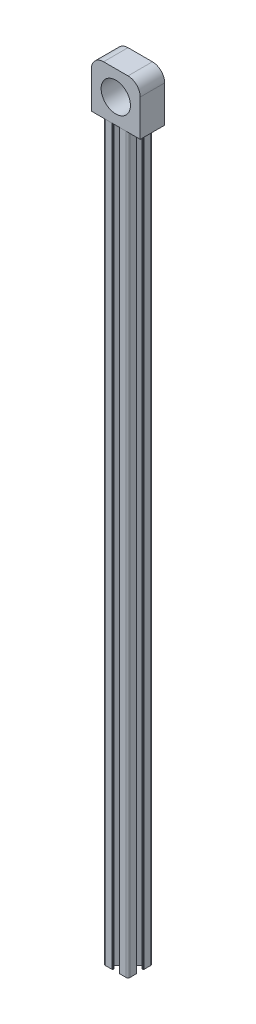
SolidWorks part; units mm, degrees
material "6061-O (SS)"
ref_plane "Front Plane" through (0, 0, 0) normal (0, 0, 1) x (1, 0, 0)
ref_plane "Top Plane" through (0, 0, 0) normal (0, 1, 0) x (1, 0, 0)
ref_plane "Right Plane" through (0, 0, 0) normal (1, 0, 0) x (0, 0, -1)
sketch "Sketch1" plane through (0, 0, 0) normal (0, 1, 0) x (1, 0, 0)
  line L0 (9.4949, 2.6581) -> (9.0109, 2.6581)
  line L1 (8.5029, 3.1661) -> (8.5029, 5.5151)
  line L2 (10.0029, 3.1661) -> (10.0029, 8.5281)
  line L3 (3.6579, -2.3558) -> (3.6579, 2.412)
  line L4 (7.269, 6.0231) -> (7.9949, 6.0231)
  line L5 (6.9098, 5.8743) -> (3.8067, 2.7712)
  line L6 (9.4949, -2.6019) -> (9.0109, -2.6019)
  line L7 (10.0029, -3.1099) -> (10.0029, -8.4719)
  line L8 (8.5029, -3.1099) -> (8.5029, -5.4589)
  line L9 (7.269, -5.9669) -> (7.9949, -5.9669)
  line L10 (6.9098, -5.8181) -> (3.8067, -2.715)
  line L11 (2.1278, -2.2764) -> (2.3074, -2.0968)
  line L12 (-2.6271, 9.5201) -> (-2.6271, 9.0361)
  line L13 (-3.1351, 10.0281) -> (-8.4971, 10.0281)
  line L14 (-3.1351, 8.5281) -> (-5.4841, 8.5281)
  line L15 (2.3868, 3.6831) -> (-2.381, 3.6831)
  line L16 (-5.9921, 7.2942) -> (-5.9921, 8.0201)
  line L17 (-5.8433, 6.935) -> (-2.7402, 3.8319)
  line L18 (2.6329, 9.5201) -> (2.6329, 9.0361)
  line L19 (3.1409, 10.0281) -> (8.5029, 10.0281)
  line L20 (3.1409, 8.5281) -> (5.4899, 8.5281)
  line L21 (5.9979, 7.2942) -> (5.9979, 8.0201)
  line L22 (5.8491, 6.935) -> (2.746, 3.8319)
  line L23 (2.3074, 2.153) -> (2.1278, 2.3326)
  line L24 (-9.4891, -2.6019) -> (-9.0051, -2.6019)
  line L25 (-9.9971, -3.1099) -> (-9.9971, -8.4719)
  line L26 (-8.4971, -3.1099) -> (-8.4971, -5.4589)
  line L27 (-3.6521, 2.412) -> (-3.6521, -2.3558)
  line L28 (-7.2632, -5.9669) -> (-7.9891, -5.9669)
  line L29 (-6.904, -5.8181) -> (-3.8009, -2.715)
  line L30 (-9.4891, 2.6581) -> (-9.0051, 2.6581)
  line L31 (-9.9971, 3.1661) -> (-9.9971, 8.5281)
  line L32 (-8.4971, 3.1661) -> (-8.4971, 5.5151)
  line L33 (-7.2632, 6.0231) -> (-7.9891, 6.0231)
  line L34 (-6.904, 5.8743) -> (-3.8009, 2.7712)
  line L35 (-2.122, 2.3326) -> (-2.3016, 2.153)
  line L36 (2.6329, -9.4639) -> (2.6329, -8.9799)
  line L37 (3.1409, -9.9719) -> (8.5029, -9.9719)
  line L38 (3.1409, -8.4719) -> (5.4899, -8.4719)
  line L39 (-2.381, -3.6269) -> (2.3868, -3.6269)
  line L40 (5.9979, -7.238) -> (5.9979, -7.9639)
  line L41 (5.8491, -6.8788) -> (2.746, -3.7757)
  line L42 (-2.6271, -9.4639) -> (-2.6271, -8.9799)
  line L43 (-3.1351, -9.9719) -> (-8.4971, -9.9719)
  line L44 (-3.1351, -8.4719) -> (-5.4841, -8.4719)
  line L45 (-5.9921, -7.238) -> (-5.9921, -7.9639)
  line L46 (-5.8433, -6.8788) -> (-2.7402, -3.7757)
  line L47 (-2.3016, -2.0968) -> (-2.122, -2.2764)
  arc A0 (-0.8011, -1.9071) -> (0.8069, -1.9071) centre (0.0029, 0.0281) ccw
  arc A1 (8.5029, 5.5151) -> (7.9949, 6.0231) centre (7.9949, 5.5151) ccw
  arc A2 (7.269, 6.0231) -> (6.9098, 5.8743) centre (7.269, 5.5151) ccw
  arc A3 (3.8067, 2.7712) -> (3.6579, 2.412) centre (4.1659, 2.412) ccw
  arc A4 (3.6579, -2.3558) -> (3.8067, -2.715) centre (4.1659, -2.3558) ccw
  arc A5 (6.9098, -5.8181) -> (7.269, -5.9669) centre (7.269, -5.4589) ccw
  arc A6 (7.9949, -5.9669) -> (8.5029, -5.4589) centre (7.9949, -5.4589) ccw
  arc A7 (9.0109, -2.6019) -> (8.5029, -3.1099) centre (9.0109, -3.1099) ccw
  arc A8 (10.0029, -3.1099) -> (9.4949, -2.6019) centre (9.4949, -3.1099) ccw
  arc A9 (9.4949, 2.6581) -> (10.0029, 3.1661) centre (9.4949, 3.1661) ccw
  arc A10 (8.5029, 3.1661) -> (9.0109, 2.6581) centre (9.0109, 3.1661) ccw
  arc A11 (0.8069, -1.9071) -> (2.1278, -2.2764) centre (1.5713, -1.7199) ccw
  arc A12 (2.3074, -2.0968) -> (1.9381, -0.7759) centre (1.7509, -1.5403) ccw
  arc A13 (-2.6271, 9.5201) -> (-3.1351, 10.0281) centre (-3.1351, 9.5201) ccw
  arc A14 (-3.1351, 8.5281) -> (-2.6271, 9.0361) centre (-3.1351, 9.0361) ccw
  arc A15 (1.9381, -0.7759) -> (1.9381, 0.8321) centre (0.0029, 0.0281) ccw
  arc A16 (-2.7402, 3.8319) -> (-2.381, 3.6831) centre (-2.381, 4.1911) ccw
  arc A17 (-5.4841, 8.5281) -> (-5.9921, 8.0201) centre (-5.4841, 8.0201) ccw
  arc A18 (-5.9921, 7.2942) -> (-5.8433, 6.935) centre (-5.4841, 7.2942) ccw
  arc A19 (2.6329, 9.0361) -> (3.1409, 8.5281) centre (3.1409, 9.0361) ccw
  arc A20 (3.1409, 10.0281) -> (2.6329, 9.5201) centre (3.1409, 9.5201) ccw
  arc A21 (5.9979, 8.0201) -> (5.4899, 8.5281) centre (5.4899, 8.0201) ccw
  arc A22 (5.8491, 6.935) -> (5.9979, 7.2942) centre (5.4899, 7.2942) ccw
  arc A23 (2.3868, 3.6831) -> (2.746, 3.8319) centre (2.3868, 4.1911) ccw
  arc A24 (1.9381, 0.8321) -> (2.3074, 2.153) centre (1.7509, 1.5965) ccw
  arc A25 (2.1278, 2.3326) -> (0.8069, 1.9632) centre (1.5713, 1.7761) ccw
  arc A26 (-9.4891, -2.6019) -> (-9.9971, -3.1099) centre (-9.4891, -3.1099) ccw
  arc A27 (-8.4971, -3.1099) -> (-9.0051, -2.6019) centre (-9.0051, -3.1099) ccw
  arc A28 (0.8069, 1.9632) -> (-0.8011, 1.9632) centre (0.0029, 0.0281) ccw
  arc A29 (-3.8009, -2.715) -> (-3.6521, -2.3558) centre (-4.1601, -2.3558) ccw
  arc A30 (-8.4971, -5.4589) -> (-7.9891, -5.9669) centre (-7.9891, -5.4589) ccw
  arc A31 (-7.2632, -5.9669) -> (-6.904, -5.8181) centre (-7.2632, -5.4589) ccw
  arc A32 (-9.0051, 2.6581) -> (-8.4971, 3.1661) centre (-9.0051, 3.1661) ccw
  arc A33 (-9.9971, 3.1661) -> (-9.4891, 2.6581) centre (-9.4891, 3.1661) ccw
  arc A34 (-7.9891, 6.0231) -> (-8.4971, 5.5151) centre (-7.9891, 5.5151) ccw
  arc A35 (-6.904, 5.8743) -> (-7.2632, 6.0231) centre (-7.2632, 5.5151) ccw
  arc A36 (-3.6521, 2.412) -> (-3.8009, 2.7712) centre (-4.1601, 2.412) ccw
  arc A37 (-0.8011, 1.9632) -> (-2.122, 2.3326) centre (-1.5655, 1.7761) ccw
  arc A38 (-2.3016, 2.153) -> (-1.9322, 0.8321) centre (-1.7451, 1.5965) ccw
  arc A39 (2.6329, -9.4639) -> (3.1409, -9.9719) centre (3.1409, -9.4639) ccw
  arc A40 (3.1409, -8.4719) -> (2.6329, -8.9799) centre (3.1409, -8.9799) ccw
  arc A41 (-1.9322, 0.8321) -> (-1.9322, -0.7759) centre (0.0029, 0.0281) ccw
  arc A42 (2.746, -3.7757) -> (2.3868, -3.6269) centre (2.3868, -4.1349) ccw
  arc A43 (5.4899, -8.4719) -> (5.9979, -7.9639) centre (5.4899, -7.9639) ccw
  arc A44 (5.9979, -7.238) -> (5.8491, -6.8788) centre (5.4899, -7.238) ccw
  arc A45 (-2.6271, -8.9799) -> (-3.1351, -8.4719) centre (-3.1351, -8.9799) ccw
  arc A46 (-3.1351, -9.9719) -> (-2.6271, -9.4639) centre (-3.1351, -9.4639) ccw
  arc A47 (-5.9921, -7.9639) -> (-5.4841, -8.4719) centre (-5.4841, -7.9639) ccw
  arc A48 (-5.8433, -6.8788) -> (-5.9921, -7.238) centre (-5.4841, -7.238) ccw
  arc A49 (-2.381, -3.6269) -> (-2.7402, -3.7757) centre (-2.381, -4.1349) ccw
  arc A50 (-1.9322, -0.7759) -> (-2.3016, -2.0968) centre (-1.7451, -1.5403) ccw
  arc A51 (-2.122, -2.2764) -> (-0.8011, -1.9071) centre (-1.5655, -1.7199) ccw
  arc A52 (10.0029, 8.5281) -> (8.5029, 10.0281) centre (8.5029, 8.5281) ccw
  arc A53 (8.5029, -9.9719) -> (10.0029, -8.4719) centre (8.5029, -8.4719) ccw
  arc A54 (-9.9971, -8.4719) -> (-8.4971, -9.9719) centre (-8.4971, -8.4719) ccw
  arc A55 (-8.4971, 10.0281) -> (-9.9971, 8.5281) centre (-8.4971, 8.5281) ccw
  point P157 (0, 0)
extrude "Boss-Extrude1" add sketch "Sketch1" along normal blind 600
sketch "Sketch2" plane through (0, 600, 0) normal (0, 1, 0) x (1, 0, 0)
  line L1 (-20, -10) -> (20, -10)
  line L2 (-20, -10) -> (-20, 10)
  line L3 (-20, 10) -> (20, 10)
  line L4 (20, -10) -> (20, 10)
  line L5 (-20, -10) -> (20, 10) construction
  line L6 (-20, 10) -> (20, -10) construction
  point P0 (0, 0)
  point P8 (0, 0)
  dimension "D1" = 20
extrude "Boss-Extrude2" add sketch "Sketch2" along normal blind 40
fillet "Fillet1" radius 10 2 edges at (-20, 640, 0) (20, 640, 0)
sketch "Sketch3" plane through (0, 0, 10) normal (0, 0, 1) x (1, 0, 0)
  line L0 (0, 600) -> (0, 640) construction
  line L3 (-20, 600) -> (20, 600) construction
  line L4 (-10, 640) -> (10, 640) construction
  circle A0 centre (0, 620) radius 12
  point P2 (0, 600)
  point P4 (0, 0)
  point P5 (0, 640)
  point P8 (0, 0)
  point P10 (0, 640)
  dimension "D1" = 24
extrude "Cut-Extrude1" cut sketch "Sketch3" against normal blind 40
